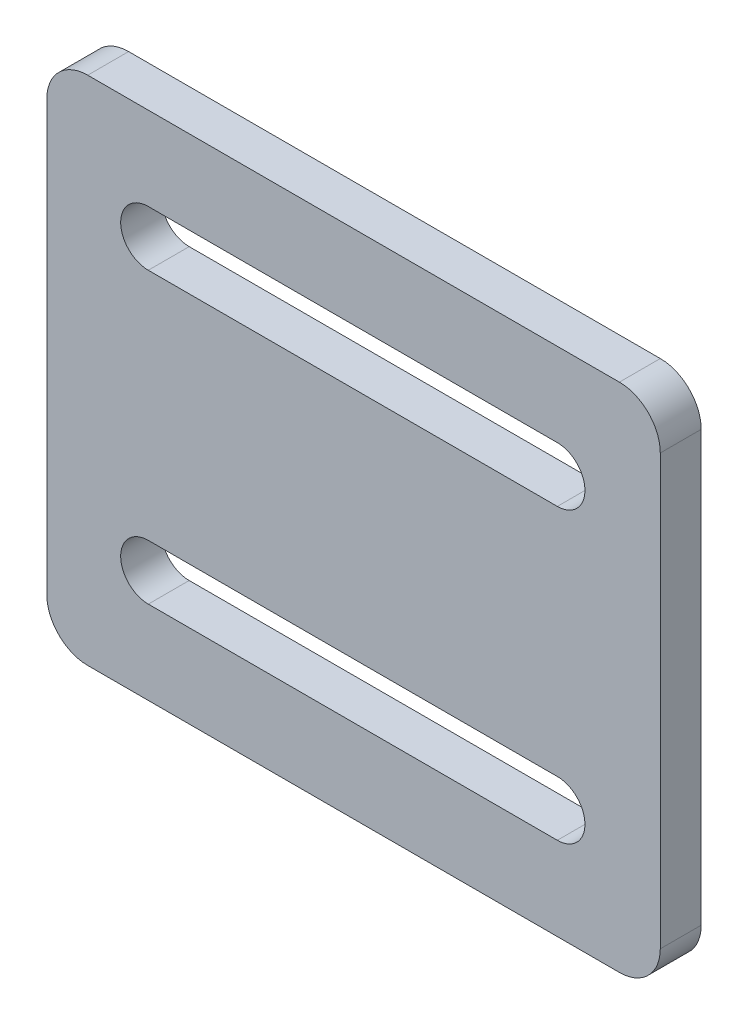
SolidWorks part; units mm, degrees
material "Thornel Mat VMA"
ref_plane "Alzado" through (0, 0, 0) normal (0, 0, 1) x (1, 0, 0)
ref_plane "Planta" through (0, 0, 0) normal (0, 1, 0) x (1, 0, 0)
ref_plane "Vista lateral" through (0, 0, 0) normal (1, 0, 0) x (0, 0, -1)
sketch "Croquis1" plane through (0, 0, 0) normal (0, 0, 1) x (1, 0, 0)
  line L0 (-51.117, 25.6331) -> (-31.1137, 25.6331)
  line L1 (-31.1137, 28.3331) -> (-51.117, 28.3331)
  line L2 (-51.117, 11.4931) -> (-31.1137, 11.4931)
  line L3 (-31.1137, 14.1931) -> (-51.117, 14.1931)
  line L4 (-26.0793, 9.4131) -> (-26.0793, 30.4131)
  line L5 (-54.0793, 7.4131) -> (-28.0793, 7.4131)
  line L6 (-28.0793, 32.4131) -> (-54.0793, 32.4131)
  line L7 (-56.0793, 30.4131) -> (-56.0793, 9.4131)
  arc A0 (-28.0793, 7.4131) -> (-26.0793, 9.4131) centre (-28.0793, 9.4131) ccw
  arc A1 (-56.0793, 9.4131) -> (-54.0793, 7.4131) centre (-54.0793, 9.4131) ccw
  arc A2 (-26.0793, 30.4131) -> (-28.0793, 32.4131) centre (-28.0793, 30.4131) ccw
  arc A3 (-54.0793, 32.4131) -> (-56.0793, 30.4131) centre (-54.0793, 30.4131) ccw
  ellipse E0 centre (-31.1137, 26.9831) end of major axis (-29.7635, 26.9831) minor radius 1.35 (-31.1137, 25.6331) -> (-31.1137, 28.3331) ccw
  ellipse E1 centre (-51.117, 26.9831) end of major axis (-52.4672, 26.9831) minor radius 1.35 (-51.117, 28.3331) -> (-51.117, 25.6331) ccw
  ellipse E2 centre (-31.1137, 12.8431) end of major axis (-32.464, 12.8431) minor radius 1.35 (-31.1137, 11.4931) -> (-31.1137, 14.1931) ccw
  ellipse E3 centre (-51.117, 12.8431) end of major axis (-52.4672, 12.8431) minor radius 1.35 (-51.117, 14.1931) -> (-51.117, 11.4931) ccw
extrude "Saliente-Extruir1" add sketch "Croquis1" along normal blind 2
